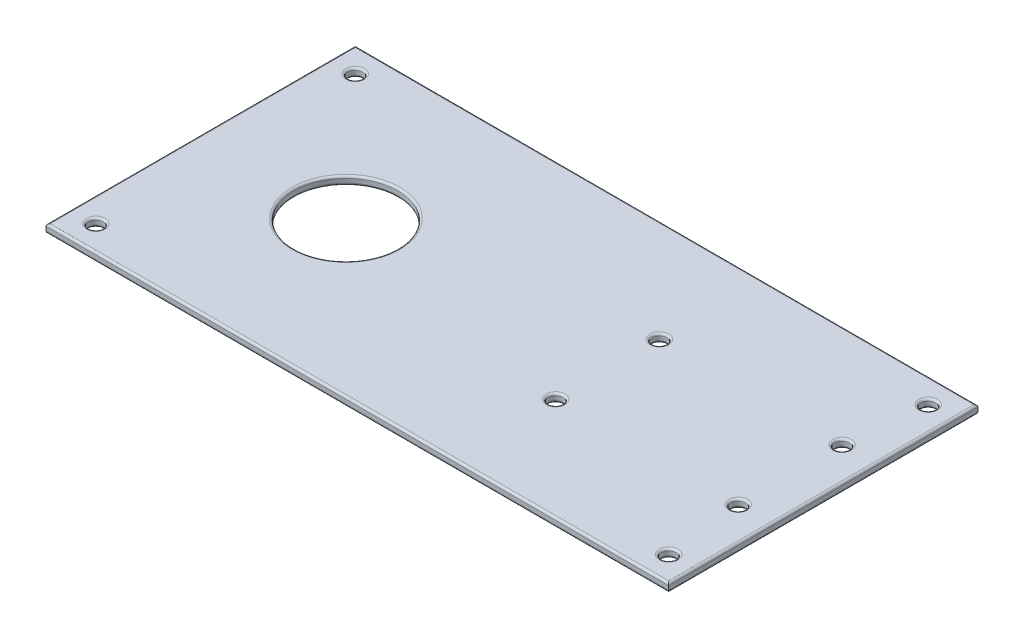
SolidWorks part; units mm, degrees
ref_plane "Front Plane" through (0, 0, 0) normal (0, 0, 1) x (1, 0, 0)
ref_plane "Top Plane" through (0, 0, 0) normal (0, 1, 0) x (1, 0, 0)
ref_plane "Right Plane" through (0, 0, 0) normal (1, 0, 0) x (0, 0, -1)
sketch "Sketch1" plane through (0, 0, 0) normal (0, 1, 0) x (1, 0, 0)
  line L0 (0, 37.25) -> (5, 37.25) construction
  line L1 (0, 0) -> (150, 0)
  line L2 (0, 0) -> (0, 74.5)
  line L3 (0, 74.5) -> (150, 74.5)
  line L4 (150, 0) -> (150, 74.5)
  line L5 (6, 74.5) -> (6, 68.5) construction
  line L6 (6, 68.5) -> (0, 68.5) construction
  line L7 (144, 0) -> (144, 6) construction
  line L8 (144, 6) -> (150, 6) construction
  line L9 (150, 68.5) -> (144, 68.5) construction
  line L10 (144, 68.5) -> (144, 74.5) construction
  line L11 (5, 37.25) -> (35, 37.25) construction
  line L12 (0, 6) -> (6, 6) construction
  line L13 (6, 6) -> (6, 0) construction
  line L14 (150, 37.25) -> (142, 37.25) construction
  line L15 (142, 37.25) -> (142, 49.75) construction
  line L16 (142, 49.75) -> (98, 49.75) construction
  line L17 (98, 49.75) -> (98, 24.75) construction
  line L18 (98, 24.75) -> (142, 24.75) construction
  line L19 (142, 24.75) -> (142, 37.25) construction
  circle A2 centre (144, 6) radius 1.75
  circle A3 centre (144, 68.5) radius 1.75
  circle A4 centre (35, 37.25) radius 12.5
  circle A5 centre (6, 68.5) radius 1.75
  circle A6 centre (6, 6) radius 1.75
  circle A7 centre (98, 49.75) radius 1.75
  circle A8 centre (142, 49.75) radius 1.75
  circle A9 centre (142, 24.75) radius 1.75
  circle A10 centre (98, 24.75) radius 1.75
  dimension "D5" = 44
  dimension "D7" = 3.5
  dimension "D8" = 25
  dimension "D11" = 3.5
  dimension "D1" = 74.5
  dimension "D2" = 150
  dimension "D3" = 5
  dimension "D4" = 8
  dimension "D6" = 6
  dimension "D9" = 30
  dimension "D10" = 25
extrude "Boss-Extrude1" add sketch "Sketch1" along normal blind 2
fillet "Fillet1" radius 0.5 26 edges at (144, 0, -66.75) (75, 0, 0) (150, 0, -37.25) (75, 0, -74.5) (0, 0, -37.25) (144, 0, -4.25) (144, 2, -66.75) (144, 2, -4.25) (75, 2, -74.5) (150, 2, -37.25) (75, 2, 0) (0, 2, -37.25) (35, 0, -24.75) (35, 2, -24.75) (6, 0, -4.25) (6, 0, -66.75) (6, 2, -4.25) (6, 2, -66.75) (98, 0, -23) (142, 0, -48) (98, 0, -48) (142, 0, -23) (98, 2, -23) (142, 2, -23) (142, 2, -48) (98, 2, -48)
